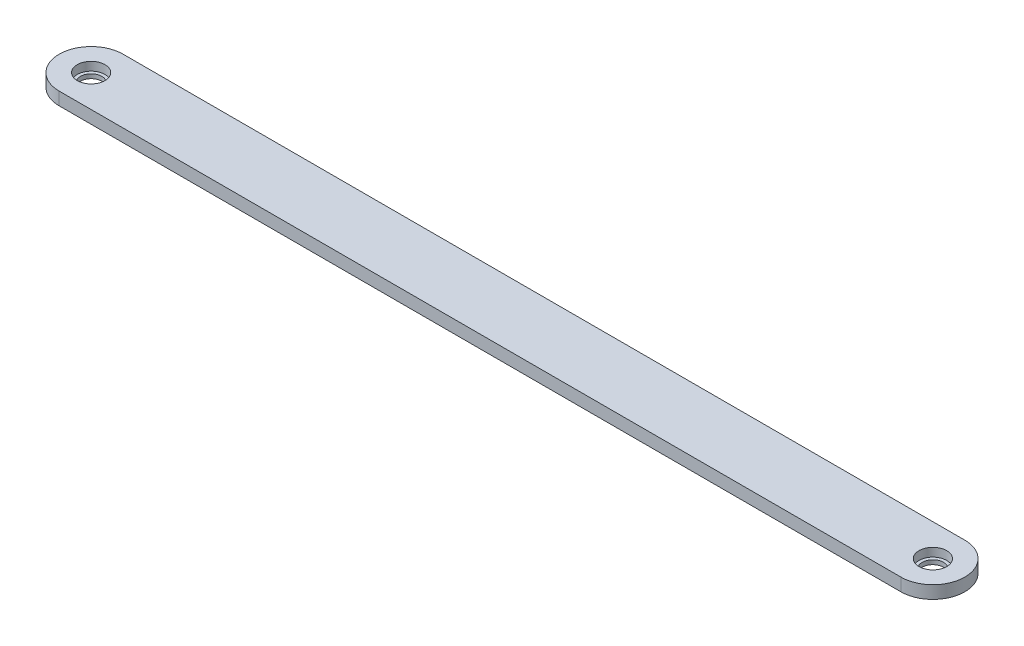
SolidWorks part; units mm, degrees
ref_plane "Front Plane" through (0, 0, 0) normal (0, 0, 1) x (1, 0, 0)
ref_plane "Top Plane" through (0, 0, 0) normal (0, 1, 0) x (1, 0, 0)
ref_plane "Right Plane" through (0, 0, 0) normal (1, 0, 0) x (0, 0, -1)
sketch "Sketch2" plane through (0, 0, 0) normal (0, 1, 0) x (1, 0, 0)
  line L1 (-45, 15) -> (350, 15)
  line L3 (-45, -15) -> (350, -15)
  arc A0 (-45, 15) -> (-45, -15) centre (-45, 0) ccw
  arc A1 (350, -15) -> (350, 15) centre (350, 0) ccw
  circle A2 centre (-45, 0) radius 5
  circle A3 centre (350, 0) radius 5
  point P0 (0, 0)
  point P7 (0, 0)
  point P9 (0, 0)
  point P12 (0, 0)
extrude "Boss-Extrude1" add sketch "Sketch2" along normal blind 6
sketch "Sketch4" plane through (0, 6, 0) normal (0, 1, 0) x (1, 0, 0)
  circle A0 centre (-45, 0) radius 6.5
  circle A1 centre (350, 0) radius 6.5
extrude "Cut-Extrude2" cut sketch "Sketch4" against normal blind 4
